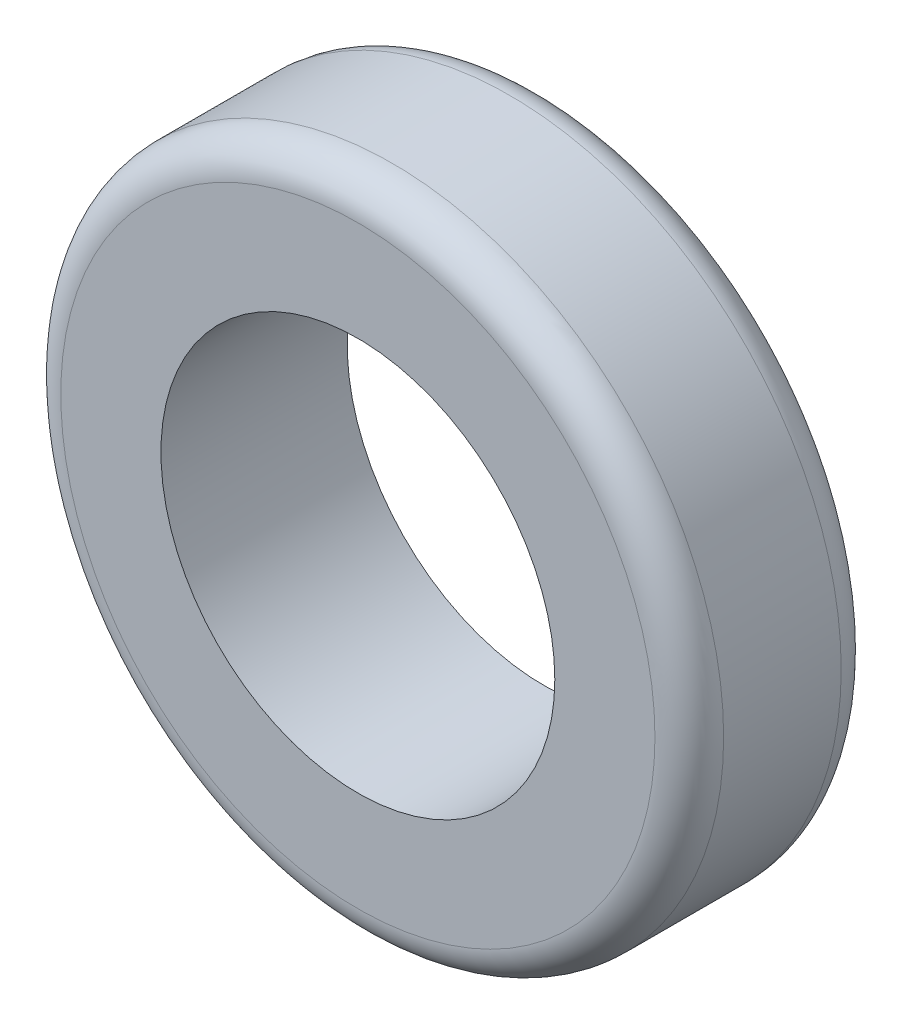
SolidWorks part; units mm, degrees
ref_plane "前视基准面" through (0, 0, 0) normal (0, 0, 1) x (1, 0, 0)
ref_plane "上视基准面" through (0, 0, 0) normal (0, 1, 0) x (1, 0, 0)
ref_plane "右视基准面" through (0, 0, 0) normal (1, 0, 0) x (0, 0, -1)
sketch "草图3" plane through (0, 0, 0) normal (0, 0, 1) x (1, 0, 0)
  circle A0 centre (58.7426, 48.9426) radius 96.5
extrude "凸台-拉伸1" add sketch "草图3" along normal blind 54.23
fillet "圆角1" radius 10 2 edges at (155.2426, 48.9426, 0) (155.2426, 48.9426, 54.23)
sketch "草图4" plane through (0, 0, 54.23) normal (0, 0, 1) x (1, 0, 0)
  circle A0 centre (58.7426, 48.9426) radius 57.34
extrude "切除-拉伸1" cut sketch "草图4" against normal blind 54.23
